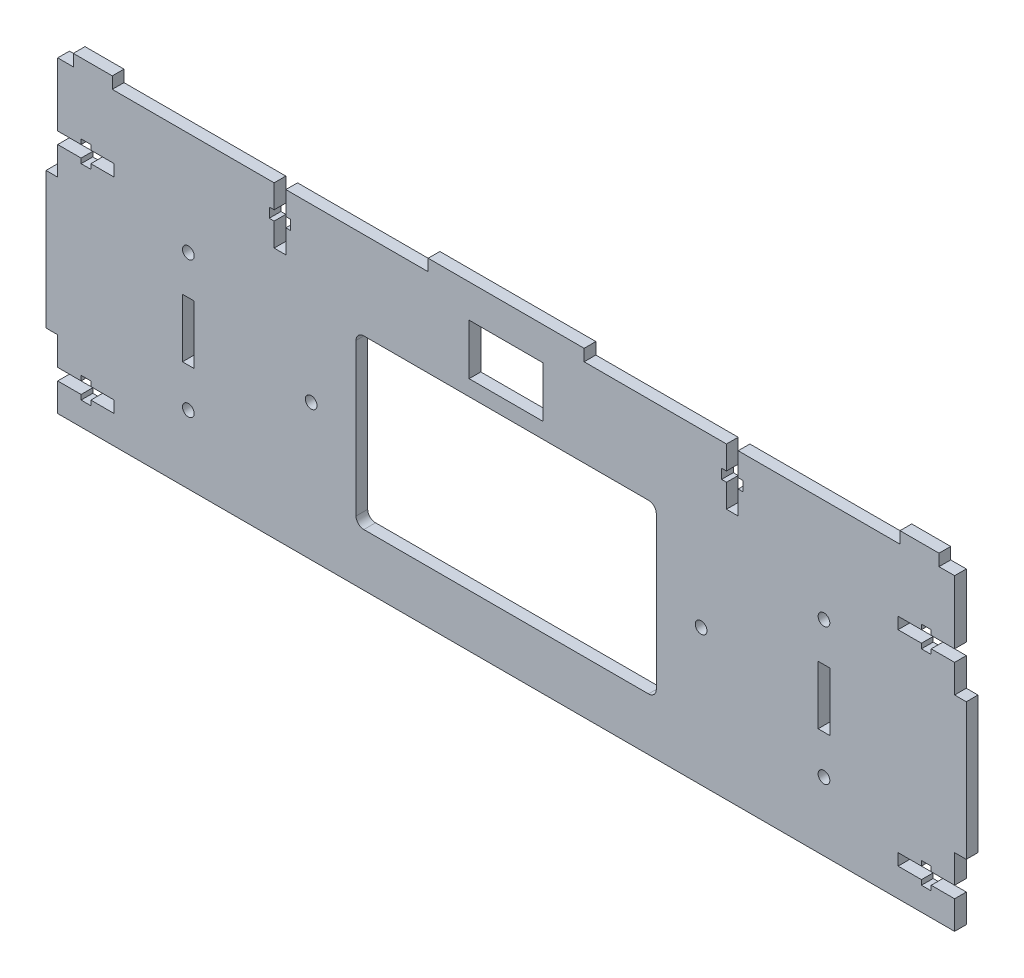
SolidWorks part; units mm, degrees
ref_plane "Спереди" through (0, 0, 0) normal (0, 0, 1) x (1, 0, 0)
ref_plane "Сверху" through (0, 0, 0) normal (0, 1, 0) x (1, 0, 0)
ref_plane "Справа" through (0, 0, 0) normal (1, 0, 0) x (0, 0, -1)
sketch "Эскиз1" plane through (0, 0, 0) normal (0, 0, 1) x (1, 0, 0)
  line L1 (0, 0) -> (230, 0)
  line L2 (0, 0) -> (0, 79)
  line L3 (0, 79) -> (230, 79)
  line L4 (230, 0) -> (230, 79)
  dimension "D1" = 79
  dimension "D2" = 230
extrude "Бобышка-Вытянуть1" add sketch "Эскиз1" along normal blind 3
sketch "Эскиз4" plane through (230, 0, 0) normal (1, 0, 0) x (0, 0, -1)
  line L0 (-3, 0) -> (-3, 79) construction
  line L1 (-3, 17.5) -> (0, 17.5)
  line L2 (-3, 17.5) -> (-3, 52.5)
  line L3 (-3, 52.5) -> (0, 52.5)
  line L4 (0, 17.5) -> (0, 52.5)
  line L5 (0, 0) -> (0, 79) construction
  point P8 (-3, 35)
  dimension "D1" = 35
  dimension "D2" = 35
extrude "Бобышка-Вытянуть2" add sketch "Эскиз4" along normal blind 3 and the other way blind 233
sketch "Эскиз2" plane through (0, 0, 3) normal (0, 0, 1) x (1, 0, 0)
  line L0 (230, 79) -> (0, 79) construction
  line L1 (0, 0) -> (230, 0) construction
  circle A0 centre (65, 35) radius 1.5
  circle A1 centre (165, 35) radius 1.5
  point P6 (115, 79)
  dimension "D1" = 3
  dimension "D2" = 100
  dimension "D3" = 50
  dimension "D4" = 35
extrude "Вырез-Вытянуть1" cut sketch "Эскиз2" against normal blind 3
sketch "Эскиз3" plane through (0, 0, 3) normal (0, 0, 1) x (1, 0, 0)
  line L0 (0, 0) -> (230, 0) construction
  circle A0 centre (33.5, 52.5) radius 1.5
  circle A1 centre (196.5, 52.5) radius 1.5
  circle A2 centre (196.5, 17.5) radius 1.5
  circle A3 centre (33.5, 17.5) radius 1.5
  point P12 (115, 0)
  dimension "D1" = 3
  dimension "D2" = 163
  dimension "D3" = 35
  dimension "D4" = 17.5
  dimension "D5" = 81.5
extrude "Вырез-Вытянуть2" cut sketch "Эскиз3" against normal blind 3
sketch "Эскиз5" plane through (0, 0, 3) normal (0, 0, 1) x (1, 0, 0)
  line L0 (0, 0) -> (230, 0) construction
  line L1 (32, 27.5) -> (35, 27.5)
  line L2 (32, 27.5) -> (32, 42.5)
  line L3 (32, 42.5) -> (35, 42.5)
  line L4 (35, 27.5) -> (35, 42.5)
  line L5 (32, 27.5) -> (35, 42.5) construction
  line L6 (32, 42.5) -> (35, 27.5) construction
  line L7 (195, 27.5) -> (198, 27.5)
  line L8 (195, 27.5) -> (195, 42.5)
  line L9 (195, 42.5) -> (198, 42.5)
  line L10 (198, 27.5) -> (198, 42.5)
  line L11 (195, 27.5) -> (198, 42.5) construction
  line L12 (195, 42.5) -> (198, 27.5) construction
  circle A0 centre (33.5, 17.5) radius 1.5 construction
  point P0 (33.5, 35)
  point P5 (196.5, 35)
  point P19 (115, 0)
  dimension "D1" = 163
  dimension "D2" = 3
  dimension "D3" = 15
  dimension "D4" = 17.5
  dimension "D5" = 81.5
extrude "Вырез-Вытянуть3" cut sketch "Эскиз5" against normal blind 3
sketch "Эскиз6" plane through (0, 0, 3) normal (0, 0, 1) x (1, 0, 0)
  line L0 (0, 10.25) -> (6, 10.25)
  line L1 (6, 10.25) -> (6, 11.5)
  line L2 (6, 11.5) -> (8.5, 11.5)
  line L3 (8.5, 11.5) -> (8.5, 10.25)
  line L4 (8.5, 10.25) -> (14.5, 10.25)
  line L5 (14.5, 10.25) -> (14.5, 7.25)
  line L6 (14.5, 7.25) -> (8.5, 7.25)
  line L7 (8.5, 7.25) -> (8.5, 6)
  line L8 (8.5, 6) -> (6, 6)
  line L9 (6, 6) -> (6, 7.25)
  line L10 (6, 7.25) -> (0, 7.25)
  line L11 (0, 7.25) -> (0, 10.25)
  line L12 (0, 17.5) -> (0, 0) construction
  line L13 (-3, 35) -> (18.5443, 35) construction
  line L14 (-3, 52.5) -> (-3, 17.5) construction
  line L15 (115, 79) -> (115, 45.2573) construction
  line L16 (230, 79) -> (0, 79) construction
  line L17 (230, 7.25) -> (230, 10.25)
  line L18 (224, 7.25) -> (230, 7.25)
  line L19 (224, 6) -> (224, 7.25)
  line L20 (221.5, 6) -> (224, 6)
  line L21 (221.5, 7.25) -> (221.5, 6)
  line L22 (215.5, 7.25) -> (221.5, 7.25)
  line L23 (215.5, 10.25) -> (215.5, 7.25)
  line L24 (221.5, 10.25) -> (215.5, 10.25)
  line L25 (221.5, 11.5) -> (221.5, 10.25)
  line L26 (224, 11.5) -> (221.5, 11.5)
  line L27 (224, 10.25) -> (224, 11.5)
  line L28 (230, 10.25) -> (224, 10.25)
  line L29 (230, 59.75) -> (224, 59.75)
  line L30 (224, 59.75) -> (224, 58.5)
  line L31 (224, 58.5) -> (221.5, 58.5)
  line L32 (221.5, 58.5) -> (221.5, 59.75)
  line L33 (221.5, 59.75) -> (215.5, 59.75)
  line L34 (215.5, 59.75) -> (215.5, 62.75)
  line L35 (215.5, 62.75) -> (221.5, 62.75)
  line L36 (221.5, 62.75) -> (221.5, 64)
  line L37 (221.5, 64) -> (224, 64)
  line L38 (224, 64) -> (224, 62.75)
  line L39 (224, 62.75) -> (230, 62.75)
  line L40 (230, 62.75) -> (230, 59.75)
  line L41 (0, 62.75) -> (0, 59.75)
  line L42 (6, 62.75) -> (0, 62.75)
  line L43 (6, 64) -> (6, 62.75)
  line L44 (8.5, 64) -> (6, 64)
  line L45 (8.5, 62.75) -> (8.5, 64)
  line L46 (14.5, 62.75) -> (8.5, 62.75)
  line L47 (14.5, 59.75) -> (14.5, 62.75)
  line L48 (8.5, 59.75) -> (14.5, 59.75)
  line L49 (8.5, 58.5) -> (8.5, 59.75)
  line L50 (6, 58.5) -> (8.5, 58.5)
  line L51 (6, 59.75) -> (6, 58.5)
  line L52 (0, 59.75) -> (6, 59.75)
  point P12 (0, 8.75)
  point P15 (0, 8.75)
  dimension "D1" = 6
  dimension "D2" = 5.5
  dimension "D3" = 3
  dimension "D4" = 2.5
extrude "Вырез-Вытянуть4" cut sketch "Эскиз6" against normal blind 3
sketch "Эскиз8" plane through (0, 79, 0) normal (0, 1, 0) x (1, 0, 0)
  line L0 (230, -3) -> (0, -3) construction
  line L1 (216, -3) -> (226, -3)
  line L2 (216, -3) -> (216, 0)
  line L3 (216, 0) -> (226, 0)
  line L4 (226, -3) -> (226, 0)
  line L5 (230, 0) -> (0, 0) construction
  line L6 (115, 0) -> (115, -9.1014) construction
  line L7 (4, -3) -> (4, 0)
  line L8 (14, 0) -> (4, 0)
  line L9 (14, -3) -> (14, 0)
  line L10 (14, -3) -> (4, -3)
  dimension "D1" = 10
  dimension "D2" = 7
extrude "Бобышка-Вытянуть3" add sketch "Эскиз8" along normal blind 3
sketch "Эскиз9" plane through (0, 79, 0) normal (0, 1, 0) x (1, 0, 0)
  line L0 (216, -3) -> (14, -3) construction
  line L1 (95, -3) -> (135, -3)
  line L2 (95, -3) -> (95, 0)
  line L3 (95, 0) -> (135, 0)
  line L4 (135, -3) -> (135, 0)
  line L5 (216, 0) -> (14, 0) construction
  point P8 (115, -3)
  point P9 (115, -3)
  dimension "D1" = 40
extrude "Бобышка-Вытянуть4" add sketch "Эскиз9" along normal blind 3
sketch "Эскиз10" plane through (0, 0, 3) normal (0, 0, 1) x (1, 0, 0)
  line L0 (55.5, 79) -> (55.5, 73)
  line L1 (55.5, 73) -> (54.25, 73)
  line L2 (54.25, 73) -> (54.25, 70.5)
  line L3 (54.25, 70.5) -> (55.5, 70.5)
  line L4 (55.5, 70.5) -> (55.5, 64.5)
  line L5 (55.5, 64.5) -> (58.5, 64.5)
  line L6 (58.5, 64.5) -> (58.5, 70.5)
  line L7 (58.5, 70.5) -> (59.75, 70.5)
  line L8 (59.75, 70.5) -> (59.75, 73)
  line L9 (59.75, 73) -> (58.5, 73)
  line L10 (58.5, 73) -> (58.5, 79)
  line L11 (58.5, 79) -> (55.5, 79)
  line L12 (95, 79) -> (14, 79) construction
  line L13 (115, 82) -> (115, 64.5) construction
  line L14 (95, 82) -> (135, 82) construction
  line L15 (171.5, 79) -> (174.5, 79)
  line L16 (171.5, 73) -> (171.5, 79)
  line L17 (170.25, 73) -> (171.5, 73)
  line L18 (170.25, 70.5) -> (170.25, 73)
  line L19 (171.5, 70.5) -> (170.25, 70.5)
  line L20 (171.5, 64.5) -> (171.5, 70.5)
  line L21 (174.5, 64.5) -> (171.5, 64.5)
  line L22 (174.5, 70.5) -> (174.5, 64.5)
  line L23 (175.75, 70.5) -> (174.5, 70.5)
  line L24 (175.75, 73) -> (175.75, 70.5)
  line L25 (174.5, 73) -> (175.75, 73)
  line L26 (174.5, 79) -> (174.5, 73)
  point P17 (57, 79)
  dimension "D1" = 6
  dimension "D2" = 3
  dimension "D3" = 5.5
  dimension "D4" = 2.5
  dimension "D5" = 60
extrude "Вырез-Вытянуть5" cut sketch "Эскиз10" against normal blind 3
sketch "Эскиз11" plane through (0, 0, 3) normal (0, 0, 1) x (1, 0, 0)
  line L0 (0, 0) -> (230, 0) construction
  line L1 (78.5, 56.5) -> (151.5, 56.5)
  line L2 (76.5, 54.5) -> (76.5, 15.5)
  line L3 (78.5, 13.5) -> (151.5, 13.5)
  line L4 (153.5, 54.5) -> (153.5, 15.5)
  line L5 (76.5, 56.5) -> (153.5, 13.5) construction
  line L6 (76.5, 13.5) -> (153.5, 56.5) construction
  line L7 (-3, 52.5) -> (-3, 17.5) construction
  arc A1 (151.5, 56.5) -> (153.5, 54.5) centre (151.5, 54.5) cw
  arc A2 (153.5, 15.5) -> (151.5, 13.5) centre (151.5, 15.5) cw
  arc A3 (78.5, 13.5) -> (76.5, 15.5) centre (78.5, 15.5) cw
  arc A4 (76.5, 54.5) -> (78.5, 56.5) centre (78.5, 54.5) cw
  point P0 (115, 35)
  point P8 (115, 0)
  point P15 (-3, 35)
  dimension "D3" = 2
  dimension "D1" = 77
  dimension "D2" = 43
extrude "Вырез-Вытянуть6" cut sketch "Эскиз11" against normal blind 3
sketch "Эскиз12" plane through (0, 0, 0) normal (0, 0, -1) x (-1, 0, 0)
  line L0 (-135, 82) -> (-95, 82) construction
  line L1 (-124.5, 60.5) -> (-105.5, 60.5)
  line L2 (-124.5, 60.5) -> (-124.5, 73.5)
  line L3 (-124.5, 73.5) -> (-105.5, 73.5)
  line L4 (-105.5, 60.5) -> (-105.5, 73.5)
  line L5 (-151.5, 56.5) -> (-78.5, 56.5) construction
  point P4 (-115, 73.5)
  point P7 (-115, 82)
  dimension "D1" = 19
  dimension "D2" = 13
  dimension "D3" = 4
extrude "Вырез-Вытянуть7" cut sketch "Эскиз12" against normal blind 10
